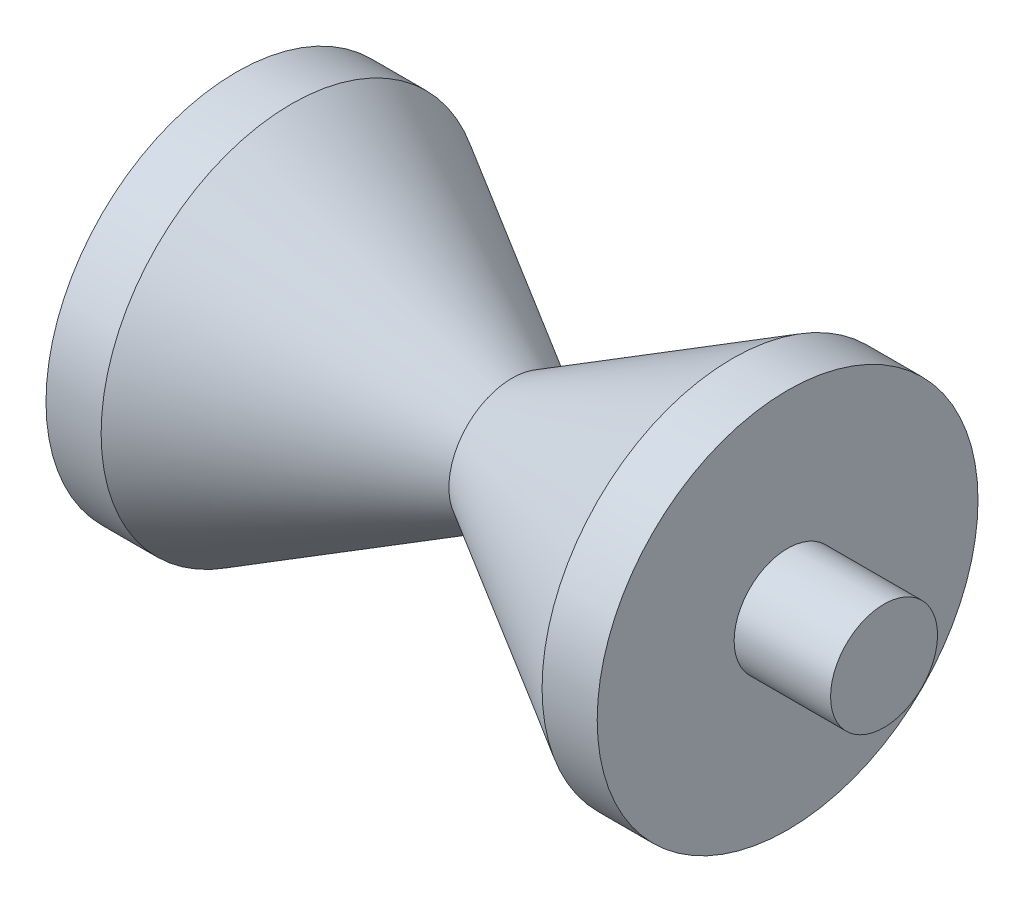
SolidWorks part; units mm, degrees
ref_plane "Front Plane" through (0, 0, 0) normal (0, 0, 1) x (1, 0, 0)
ref_plane "Top Plane" through (0, 0, 0) normal (0, 1, 0) x (1, 0, 0)
ref_plane "Right Plane" through (0, 0, 0) normal (1, 0, 0) x (0, 0, -1)
sketch "Sketch1" plane through (0, 0, 0) normal (0, 0, 1) x (1, 0, 0)
  line L0 (0, 0) -> (0, 1.145)
  line L1 (0, 1.145) -> (4, 3.4544)
  line L2 (4, 3.4544) -> (4, 0)
  line L3 (4, 0) -> (5, 0)
  line L4 (5, 0) -> (5, 3.4544)
  line L5 (5, 3.4544) -> (4, 3.4544)
  line L6 (5, 0) -> (6.75, 0)
  line L7 (6.75, 0) -> (6.75, 0.97)
  line L8 (6.75, 0.97) -> (5, 0.97)
  line L9 (0, 0) -> (4, 0)
  point P3 (4.3186, 4.4747)
  dimension "D1" = 0.97
  dimension "D2" = 1.145
  dimension "D3" = 5
  dimension "D4" = 1.75
  dimension "D5" = 60
  dimension "D6" = 1
revolve "Revolve1" add sketch "Sketch1" angle 360 about L9
mirror "Mirror1" about plane through (0, 0, 0) normal (1, 0, 0) of "Revolve1"
